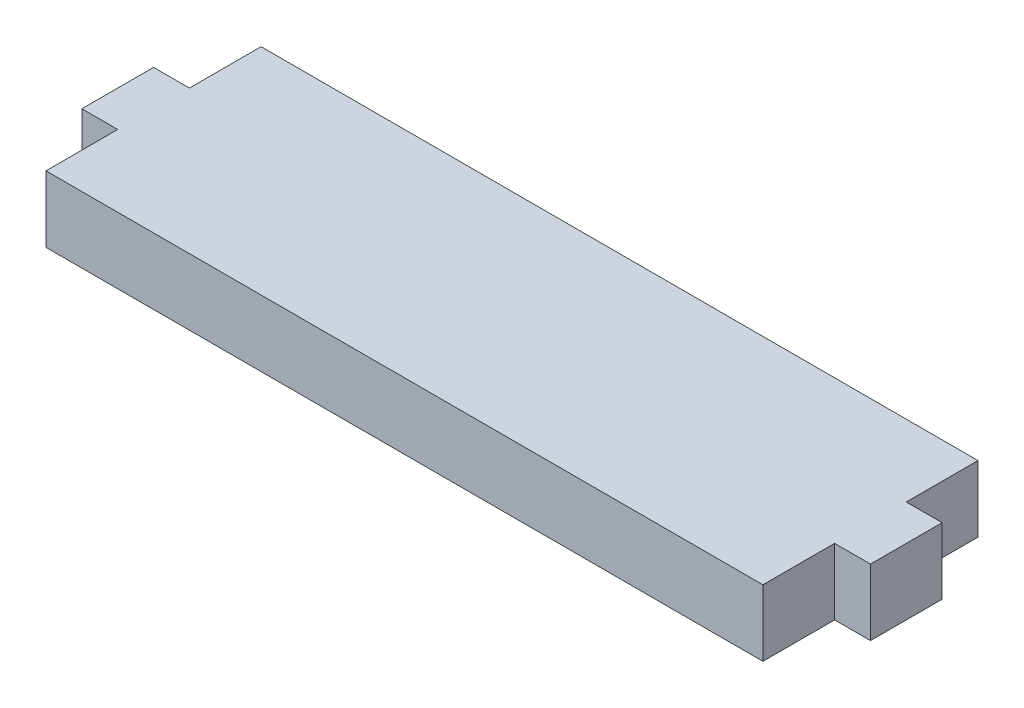
SolidWorks part; units mm, degrees
ref_plane "Front Plane" through (0, 0, 0) normal (0, 0, 1) x (1, 0, 0)
ref_plane "Top Plane" through (0, 0, 0) normal (0, 1, 0) x (1, 0, 0)
ref_plane "Right Plane" through (0, 0, 0) normal (1, 0, 0) x (0, 0, -1)
sketch "Sketch1" plane through (0, 0, 0) normal (0, 1, 0) x (1, 0, 0)
  line L1 (-17.3306, 7.4008) -> (24.6694, 7.4008)
  line L2 (-17.3306, 7.4008) -> (-17.3306, -4.5992)
  line L3 (-17.3306, 3.4008) -> (24.6694, 3.4008)
  line L4 (24.6694, 7.4008) -> (24.6694, -4.5992)
  line L5 (-17.3306, 7.4008) -> (10.77, -4.5992) construction
  line L6 (-15.3306, -4.5992) -> (24.6694, 7.4008) construction
  line L7 (24.6694, 7.4008) -> (-17.3306, 7.4008)
  line L8 (24.6694, 7.4008) -> (24.6694, 3.4008)
  line L9 (24.6694, 3.4008) -> (-17.3306, 3.4008)
  line L10 (-17.3306, 7.4008) -> (-17.3306, 3.4008)
  line L11 (-17.3306, 3.4008) -> (24.6694, 3.4008)
  line L12 (-17.3306, 3.4008) -> (-17.3306, -0.5992)
  line L13 (-17.3306, -0.5992) -> (24.6694, -0.5992)
  line L14 (24.6694, 3.4008) -> (24.6694, -0.5992)
  line L15 (-17.3306, -0.5992) -> (24.6694, -0.5992)
  line L16 (-17.3306, -0.5992) -> (-17.3306, -4.5992)
  line L17 (-17.3306, -4.5992) -> (24.6694, -4.5992)
  line L18 (24.6694, -0.5992) -> (24.6694, -4.5992)
  line L19 (-17.3306, 3.4008) -> (-17.3306, -0.5992)
  line L20 (-17.3306, -0.5992) -> (24.6694, -0.5992)
  line L21 (24.6694, 3.4008) -> (24.6694, -0.5992)
  line L22 (24.6694, 7.4008) -> (-15.3306, 7.4008)
  line L23 (24.6694, 7.4008) -> (24.6694, 3.4008)
  line L24 (24.6694, 3.4008) -> (-15.3306, 3.4008)
  line L25 (-15.3306, 7.4008) -> (-15.3306, 3.4008)
  line L26 (24.6694, 3.4008) -> (26.6694, 3.4008)
  line L27 (24.6694, 3.4008) -> (24.6694, -0.5992)
  line L28 (24.6694, -0.5992) -> (26.6694, -0.5992)
  line L29 (26.6694, 3.4008) -> (26.6694, -0.5992)
  line L30 (-17.3306, -0.5992) -> (-15.3306, -0.5992)
  line L31 (-17.3306, -0.5992) -> (-17.3306, -4.5992)
  line L32 (-17.3306, -4.5992) -> (-15.3306, -4.5992)
  line L33 (-15.3306, -0.5992) -> (-15.3306, -4.5992)
  point P0 (0, 0)
  dimension "D1" = 40
  dimension "D2" = 42
  dimension "D3" = 4
  dimension "D4" = 4
  dimension "D5" = 4
  dimension "D6" = 2
  dimension "D7" = 2
extrude "Boss-Extrude1" add sketch "Sketch1" along normal blind 3.7 contours L2 L13 L20 L4 L11 L3 | L20 L33 L17 L4 | L29 L26 L4 L28 | L7 L25 L11 L4
